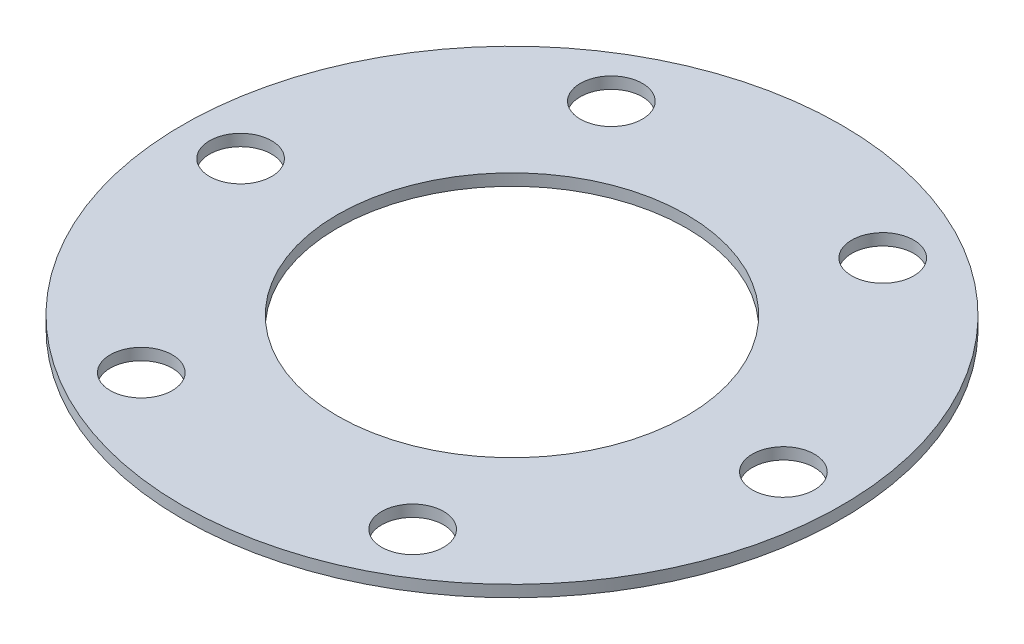
SolidWorks part; units mm, degrees
ref_plane "Front Plane" through (0, 0, 0) normal (0, 0, 1) x (1, 0, 0)
ref_plane "Top Plane" through (0, 0, 0) normal (0, 1, 0) x (1, 0, 0)
ref_plane "Right Plane" through (0, 0, 0) normal (1, 0, 0) x (0, 0, -1)
sketch "Sketch1" plane through (0, 0, 0) normal (0, 1, 0) x (1, 0, 0)
  circle A0 centre (0, 0) radius 45
  circle A1 centre (0, 0) radius 85
  dimension "D1" = 90
  dimension "D2" = 170
extrude "Boss-Extrude1" add sketch "Sketch1" along normal mid plane 3
sketch "Sketch2" plane through (0, 1.5, 0) normal (0, 1, 0) x (1, 0, 0)
  circle A0 centre (0, 0) radius 70 construction
  circle A1 centre (70, 0) radius 8
  circle A2 centre (35, -60.6218) radius 8
  circle A3 centre (-35, -60.6218) radius 8
  circle A4 centre (-70, 0) radius 8
  circle A5 centre (-35, 60.6218) radius 8
  circle A6 centre (35, 60.6218) radius 8
  point P5 (38.1519, 65.9636)
  point P6 (0, 0)
  point P18 (0, 0)
  dimension "D1" = 140
  dimension "D2" = 16
  dimension "D3" = 6
extrude "Cut-Extrude1" cut sketch "Sketch2" against normal through all both
